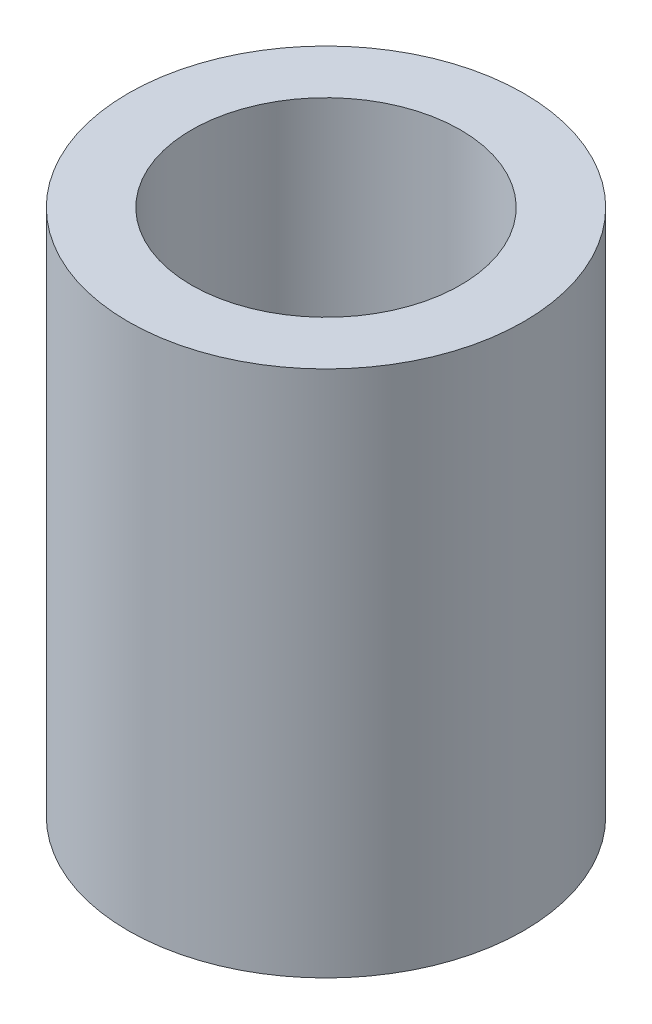
SolidWorks part; units mm, degrees
material "6061-T6 (SS)"
ref_plane "Front Plane" through (0, 0, 0) normal (0, 0, 1) x (1, 0, 0)
ref_plane "Top Plane" through (0, 0, 0) normal (0, 1, 0) x (1, 0, 0)
ref_plane "Right Plane" through (0, 0, 0) normal (1, 0, 0) x (0, 0, -1)
sketch "Sketch1" plane through (0, 0, 0) normal (0, 1, 0) x (1, 0, 0)
  circle A0 centre (0, 0) radius 4.7625
  circle A1 centre (0, 0) radius 3.2385
  dimension "D1" = 9.525
  dimension "D2" = 6.477
extrude "Boss-Extrude1" add sketch "Sketch1" along normal mid plane 12.7
